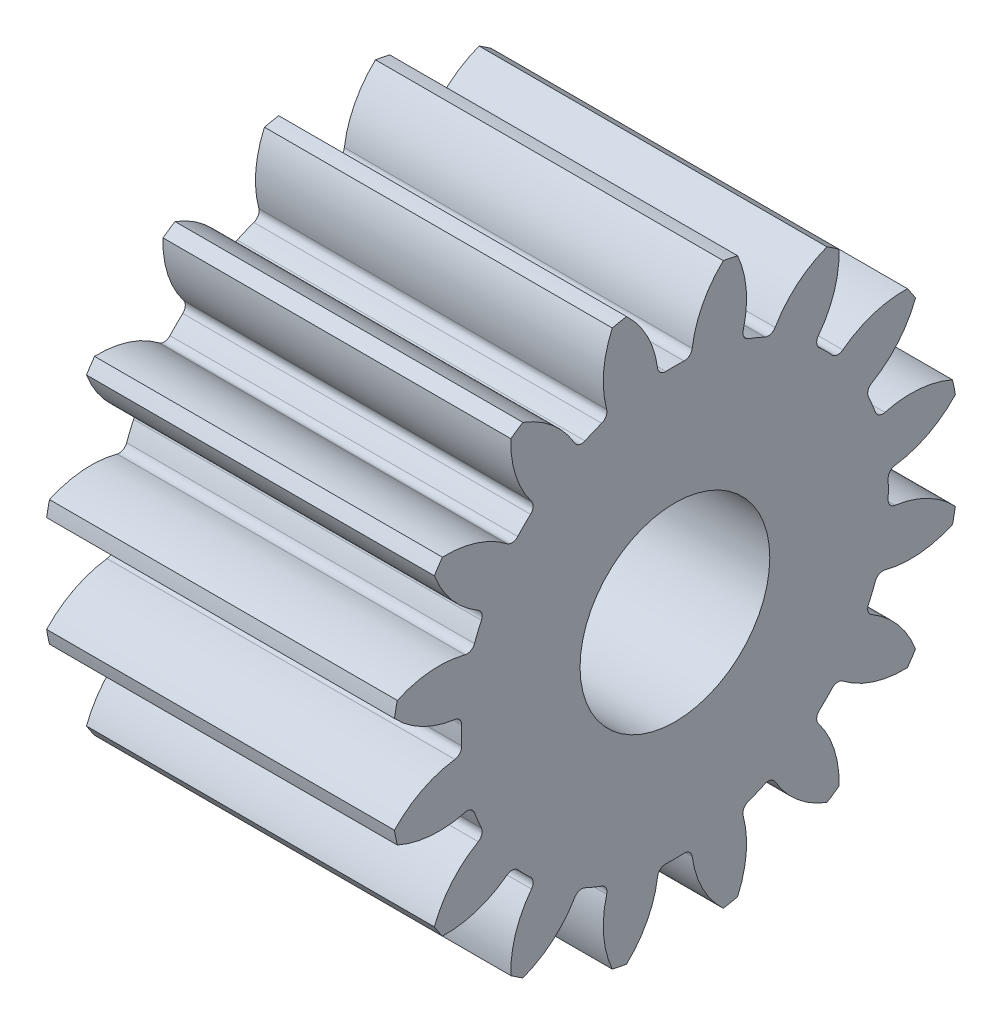
SolidWorks part; units mm, degrees
other "GearB3" parameters "Num_teeth"=16
material "Nylon 101"
ref_plane "Plane1" through (0, 0, 0) normal (0, 0, 1) x (1, 0, 0)
ref_plane "Plane2" through (0, 0, 0) normal (0, 1, 0) x (1, 0, 0)
ref_plane "Plane3" through (0, 0, 0) normal (1, 0, 0) x (0, 0, -1)
sketch "BasProSke" plane through (0, 0, 0) normal (0, 1, 0) x (1, 0, 0)
  line L0 (-10, 0) -> (60, 0) construction
  line L1 (0, 0) -> (0, 4.5)
  line L2 (0, 0) -> (5.5, 0)
  line L3 (5.5, 0) -> (5.5, 4.5)
  line L4 (5.5, 4.5) -> (0, 4.5)
  dimension "Diameter" = 9
  dimension "Thickness" = 5.5
revolve "Base-Revolve" add sketch "BasProSke" angle 360 about L0
sketch "TooCutSke" plane through (0, 0, 0) normal (1, 0, 0) x (0, 0, -1)
  line L1 (0, 0) -> (0, 107) construction
  line L2 (0, 0) -> (-0.4253, 3.9773) construction
  line L3 (0, 0) -> (-1.5544, 7.8146) construction
  line L4 (-0.4253, 3.9773) -> (-0.7772, 3.9073) construction
  arc A0 (0.2619, 3.3638) -> (-0.2619, 3.3638) centre (0, 0) ccw
  arc A1 (0.7886, 4.4562) -> (-0.7886, 4.4562) centre (0, 0) ccw
  circle A2 centre (0, 0) radius 4 construction
  circle A3 centre (0, 0) radius 3.7588 construction
  arc A4 (-0.2619, 3.3638) -> (-0.7886, 4.4562) centre (-1.8589, 3.2669) ccw
  arc A5 (0.7886, 4.4562) -> (0.2619, 3.3638) centre (1.8589, 3.2669) ccw
  dimension "Root_dia" = 6.748
  dimension "Overcut_dia" = 9.0508
  dimension "Pitch_dia" = 8
  dimension "Base_dia" = 7.5175
  dimension "Flank_rad" = 1.6
  dimension "Half_ang" = 11.25
  dimension "Half_CT" = 0.3588
extrude "ToothCut" cut sketch "TooCutSke" along normal through all
fillet "RootFillets" radius 0.126 2 edges at (2.75, 3.3638, -0.2619) (2.75, 3.3638, 0.2619)
pattern_circular "TeethCuts" count 16 over 360 about axis through (0, 0, 0) along (1, 0, 0) of "ToothCut", "RootFillets"
sketch "HoleSke" plane through (5.5, 0, 0) normal (1, 0, 0) x (0, 0, -1)
  circle A1 centre (0, 0) radius 1.5
  dimension "D1" = 3
extrude "Hole" cut sketch "HoleSke" against normal through all
equation "' \"Module@HoldingSke\" = 6.35"
equation "' \"Num_teeth@HoldingSke\" = 12"
equation "' \"Ap@HoldingSke\" =  20"
equation "' \"Ap@HoldingSke\" = 20"
equation "' \"Width@HoldingSke\" = 0.5 * 25.4"
equation "' \"Hub_dia@HoldingSke\"= 1 * 25.4"
equation "' \"Hub_dia@HoldingSke\" = 1 * 25.4"
equation "' \"Overall_len@HoldingSke\" = 1.0 * 25.4"
equation "' \"Bore@HoldingSke\" = 0.75 * 25.4"
equation "' \"T_dim@HoldingSke\" = 0.1 * 25.4"
equation "' \"Width@KeySke\" = 0.25 * 25.4"
equation "' \"Show_teeth@HoldingSke\" = 13"
equation "' \"Backlash@HoldingSke\" = 0.009 * 25.4"
equation "' \"Addendum_fac@HoldingSke\" = 1.0"
equation "' \"Dedendum_fac@HoldingSke\" = 1.25"
equation "' \"Dedendum_add@HoldingSke\" = 0.00005 * 25.4"
equation "' \"Clearance_fac@HoldingSke\" = 0.25"
equation "\"OAL@HoldingSke\" = \"Thickness@HoldingSke\""
equation "\"MHD@HoldingSke\" = (\"Num_teeth@HoldingSke\" + 2) / \"Pitch@HoldingSke\" - 2 * (\"Addendum_fac@HoldingSke\" + \"Dedendum_fac@HoldingSke\")  / \"Pitch@HoldingSke\" - \"Dedendum_add@HoldingSke\" * 2"
equation "\"MBD@HoldingSke\" = (\"Num_teeth@HoldingSke\" + 2) / \"Pitch@HoldingSke\" - 2 * (\"Addendum_fac@HoldingSke\" + \"Dedendum_fac@HoldingSke\")  / \"Pitch@HoldingSke\" - \"Dedendum_add@HoldingSke\" * 2 - 0.002 * 25.4"
equation "\"MHD@HoldingSke\" = ((sgn( \"MHD@HoldingSke\" - \"Hub_dia@HoldingSke\" )-1)*( \"MHD@HoldingSke\" - \"Hub_dia@HoldingSke\" ))/-2+ \"Hub_dia@HoldingSke\""
equation "\"Num_teeth@TeethCuts\" = int( \"Show_teeth@HoldingSke\" ) + 1"
equation "\"Num_teeth@TeethCuts\" = ((sgn( \"Num_teeth@TeethCuts\" - \"Num_teeth@HoldingSke\" )-1)*( \"Num_teeth@TeethCuts\" - \"Num_teeth@HoldingSke\" ))/-2+ \"Num_teeth@HoldingSke\""
equation "\"Num_teeth@TeethCuts\"= 16"
